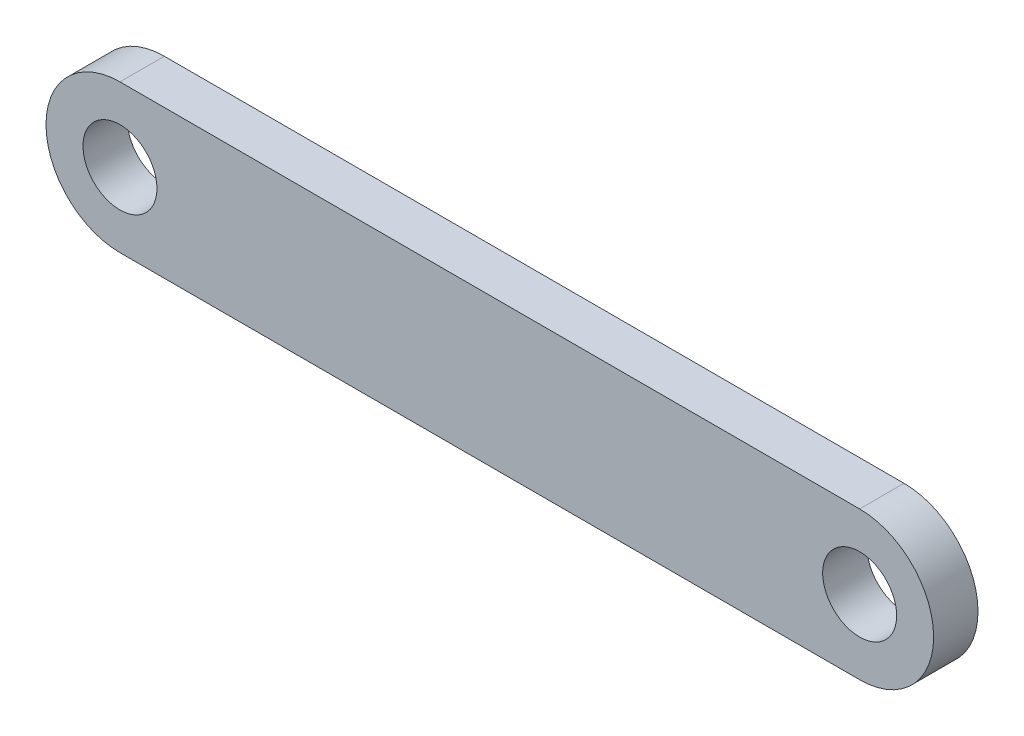
SolidWorks part; units mm, degrees
ref_plane "Front Plane" through (0, 0, 0) normal (0, 0, 1) x (1, 0, 0)
ref_plane "Top Plane" through (0, 0, 0) normal (0, 1, 0) x (1, 0, 0)
ref_plane "Right Plane" through (0, 0, 0) normal (1, 0, 0) x (0, 0, -1)
sketch "Sketch1" plane through (0, 0, 0) normal (0, 0, 1) x (1, 0, 0)
  line L0 (-25, 0) -> (25, 0) construction
  line L1 (-25, 5) -> (25, 5)
  line L2 (-25, -5) -> (25, -5)
  arc A0 (-25, 5) -> (-25, -5) centre (-25, 0) ccw
  arc A1 (25, -5) -> (25, 5) centre (25, 0) ccw
  point P2 (0, 0)
  dimension "D2" = 5
  dimension "D1" = 50
extrude "Boss-Extrude1" add sketch "Sketch1" along normal mid plane 3
sketch "Sketch2" plane through (0, 0, 1.5) normal (0, 0, 1) x (1, 0, 0)
  circle A0 centre (-25, 0) radius 2.5
  circle A1 centre (25, 0) radius 2.5
  dimension "D1" = 5
  dimension "D2" = 5
extrude "Cut-Extrude1" cut sketch "Sketch2" against normal through all
